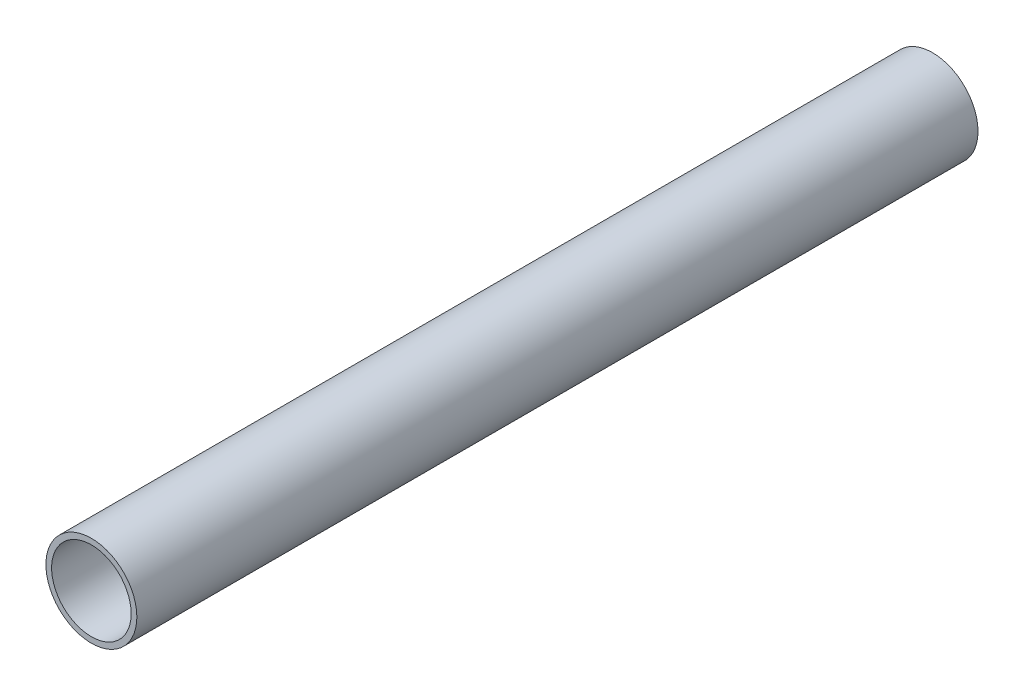
SolidWorks part; units mm, degrees
ref_plane "Front Plane" through (0, 0, 0) normal (0, 0, 1) x (1, 0, 0)
ref_plane "Top Plane" through (0, 0, 0) normal (0, 1, 0) x (1, 0, 0)
ref_plane "Right Plane" through (0, 0, 0) normal (1, 0, 0) x (0, 0, -1)
sketch "Sketch1" plane through (0, 0, 0) normal (0, 0, 1) x (1, 0, 0)
  circle A0 centre (0, 0) radius 2
  dimension "D1" = 4
extrude "Boss-Extrude1" add sketch "Sketch1" along normal mid plane 37
sketch "Sketch2" plane through (0, 0, 18.5) normal (0, 0, 1) x (1, 0, 0)
  circle A0 centre (0, 0) radius 1.75
  circle A1 centre (0, 0) radius 2 construction
  dimension "D1" = 3.5
extrude "Cut-Extrude1" cut sketch "Sketch2" against normal through all
